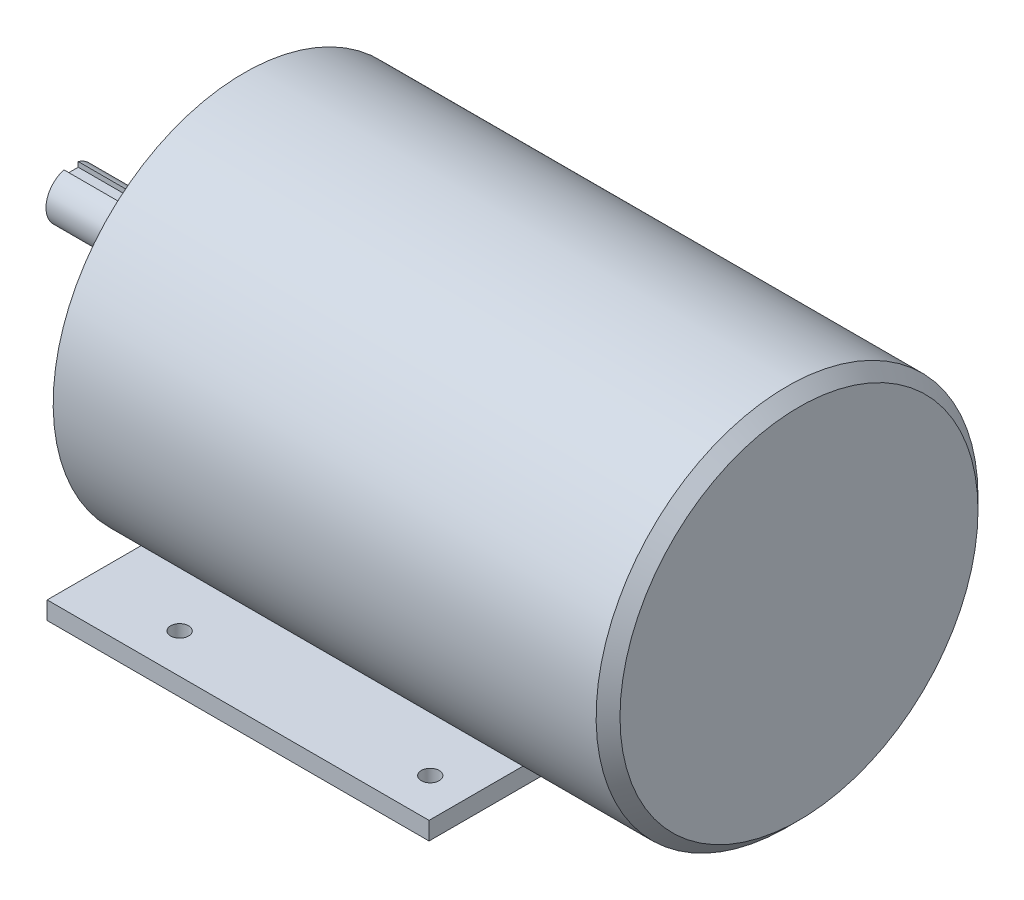
SolidWorks part; units mm, degrees
ref_plane "Front Plane" through (0, 0, 0) normal (0, 0, 1) x (1, 0, 0)
ref_plane "Top Plane" through (0, 0, 0) normal (0, 1, 0) x (1, 0, 0)
ref_plane "Right Plane" through (0, 0, 0) normal (1, 0, 0) x (0, 0, -1)
sketch "Sketch1" plane through (0, 0, 0) normal (1, 0, 0) x (0, 0, -1)
  circle A0 centre (0, 0) radius 21
  dimension "D1" = 42
extrude "Boss-Extrude1" add sketch "Sketch1" along normal blind 110
sketch "Sketch2" plane through (110, 0, 0) normal (1, 0, 0) x (0, 0, -1)
  circle A0 centre (0, 0) radius 160
  dimension "D1" = 320
extrude "Boss-Extrude2" add sketch "Sketch2" along normal blind 500
ref_plane "Plane1" through (0, -160, 0) normal (0, 1, 0) x (1, 0, 0)
sketch "Sketch3" plane through (0, -160, 0) normal (0, 1, 0) x (1, 0, 0)
  line L0 (0, 21) -> (0, -21) construction
  line L1 (140, -160) -> (460, -160)
  line L2 (140, -160) -> (140, 160)
  line L3 (140, 160) -> (460, 160)
  line L4 (460, -160) -> (460, 160)
  line L5 (140, -160) -> (460, 160) construction
  line L6 (140, 160) -> (460, -160) construction
  point P0 (300, 0)
  dimension "D1" = 320
  dimension "D2" = 320
  dimension "D3" = 0
  dimension "D4" = 300
extrude "Boss-Extrude3" add sketch "Sketch3" along normal blind 15
sketch "Sketch4" plane through (0, -160, 0) normal (0, -1, 0) x (1, 0, 0)
  circle A0 centre (428, 127) radius 7.5
  circle A1 centre (218, 127) radius 7.5
  circle A2 centre (218, -127) radius 7.5
  circle A3 centre (428, -127) radius 7.5
  point P0 (323, 0)
  dimension "D5" = 15
  dimension "D6" = 15
  dimension "D7" = 15
  dimension "D8" = 15
  dimension "D1" = 254
  dimension "D2" = 210
  dimension "D3" = 0
extrude "Cut-Extrude1" cut sketch "Sketch4" against normal blind 15
chamfer "Chamfer1" distance 10 angle 45 2 edges at (110, 0, -160) (610, 0, -160)
sketch "Sketch5" plane through (0, 0, 0) normal (0, 0, 1) x (1, 0, 0)
  line L0 (110, 37.0561) -> (115.5681, 53.947)
  line L1 (110, 150) -> (110, -150) construction
  line L2 (115.5681, 53.947) -> (126.3168, 69.3024)
  line L3 (126.3168, 69.3024) -> (136.8972, 84.4173)
  line L4 (136.8972, 84.4173) -> (136.8972, 105.1316)
  line L5 (136.8972, 105.1316) -> (145.0216, 129.7772)
  line L6 (145.0216, 129.7772) -> (145.0216, 165.5294)
  line L7 (145.0216, 165.5294) -> (110, 165.5294)
  line L8 (110, 165.5294) -> (110, 37.0561)
  line L9 (0, 0) -> (-39.3283, 0)
revolve "Cut-Revolve1" cut sketch "Sketch5" angle 360 about L9
ref_plane "Plane2" through (0, 21, 0) normal (0, 1, 0) x (1, 0, 0)
sketch "Sketch6" plane through (0, 21, 0) normal (0, 1, 0) x (1, 0, 0)
  line L0 (104, 6) -> (0, 6)
  line L1 (0, 21) -> (0, -21) construction
  line L2 (104, -6) -> (0, -6)
  line L3 (0, 6) -> (0, -6)
  arc A0 (104, -6) -> (104, 6) centre (104, 0) ccw
  dimension "D1" = 12
  dimension "D2" = 104
extrude "Cut-Extrude2" cut sketch "Sketch6" against normal blind 5
sketch "Sketch7" plane through (0, 0, 0) normal (-1, 0, 0) x (0, 0, 1)
  circle A0 centre (0, 0) radius 6
  dimension "D1" = 12
extrude "Cut-Extrude3" cut sketch "Sketch7" against normal blind 50
